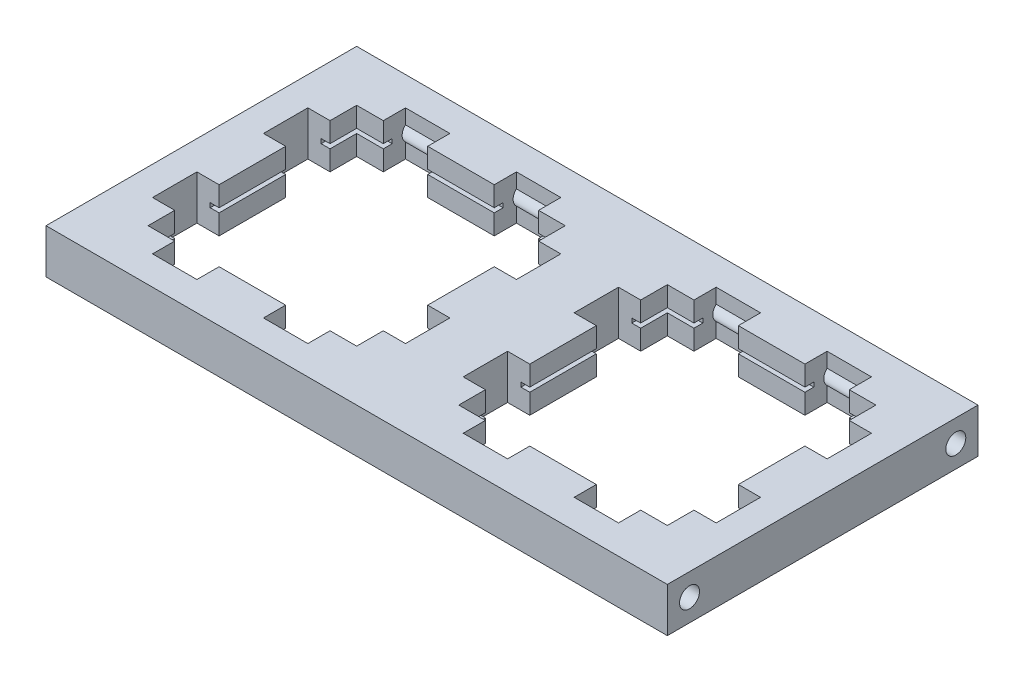
SolidWorks part; units mm, degrees
ref_plane "Front Plane" through (0, 0, 0) normal (0, 0, 1) x (1, 0, 0)
ref_plane "Top Plane" through (0, 0, 0) normal (0, 1, 0) x (1, 0, 0)
ref_plane "Right Plane" through (0, 0, 0) normal (1, 0, 0) x (0, 0, -1)
sketch "Sketch1" plane through (0, 0, 0) normal (0, 1, 0) x (1, 0, 0)
  line L1 (-70, -35) -> (70, -35)
  line L2 (-70, -35) -> (-70, 35)
  line L3 (-70, 35) -> (70, 35)
  line L4 (70, -35) -> (70, 35)
  line L5 (-70, -35) -> (70, 35) construction
  line L6 (-70, 35) -> (70, -35) construction
  point P0 (0, 0)
  dimension "D1" = 70
  dimension "D2" = 140
extrude "Boss-Extrude1" add sketch "Sketch1" along normal mid plane 10
sketch "Sketch2" plane through (70, 0, 0) normal (1, 0, 0) x (0, 0, -1)
  line L0 (-30, 0) -> (30, 0) construction
  line L1 (-35, 5) -> (-30, 0) construction
  circle A0 centre (-30, 0) radius 2.25
  circle A1 centre (30, 0) radius 2.25
  dimension "D1" = 4.5
  dimension "D2" = 45
extrude "Cut-Extrude1" cut sketch "Sketch2" against normal through all
sketch "Sketch3" plane through (0, 0, 0) normal (0, 1, 0) x (1, 0, 0)
  line L0 (-70, 35) -> (-9.5, -25.5) construction
  line L1 (-60.5, 25.5) -> (-9.5, 25.5)
  line L2 (-60.5, 25.5) -> (-60.5, -25.5)
  line L3 (-60.5, -25.5) -> (-9.5, -25.5)
  line L4 (-9.5, 25.5) -> (-9.5, -25.5)
  point P4 (-9.5, 0)
  dimension "D1" = 51
extrude "Cut-Extrude2" cut sketch "Sketch3" against normal mid plane 1
sketch "Sketch4" plane through (0, 5, 0) normal (0, 1, 0) x (1, 0, 0)
  line L8 (-11.5, 23.5) -> (-58.5, 23.5)
  line L9 (-11.5, -23.5) -> (-11.5, 23.5)
  line L10 (-58.5, -23.5) -> (-11.5, -23.5)
  line L11 (-58.5, 23.5) -> (-58.5, -23.5)
  line L12 (-11.5, 23.5) -> (-58.5, 23.5)
  line L13 (-11.5, -23.5) -> (-11.5, 23.5)
  line L14 (-58.5, -23.5) -> (-11.5, -23.5)
  line L15 (-58.5, 23.5) -> (-58.5, -23.5)
  dimension "D1" = 2
extrude "Cut-Extrude3" cut sketch "Sketch4" against normal through all
sketch "Sketch5" plane through (0, 5, 0) normal (0, 1, 0) x (1, 0, 0)
  line L0 (-11.5, 23.5) -> (-58.5, 23.5) construction
  line L1 (-52.5, 23.5) -> (-42.5, 23.5)
  line L2 (-52.5, 23.5) -> (-52.5, 28.5)
  line L3 (-52.5, 28.5) -> (-42.5, 28.5)
  line L4 (-42.5, 23.5) -> (-42.5, 28.5)
  line L5 (-11.5, -23.5) -> (-11.5, 23.5) construction
  line L6 (-27.5, 23.5) -> (-17.5, 23.5)
  line L7 (-27.5, 23.5) -> (-27.5, 28.5)
  line L8 (-27.5, 28.5) -> (-17.5, 28.5)
  line L9 (-17.5, 23.5) -> (-17.5, 28.5)
  line L10 (-11.5, 17.5) -> (-6.5, 17.5)
  line L11 (-11.5, 17.5) -> (-11.5, 7.5)
  line L12 (-11.5, 7.5) -> (-6.5, 7.5)
  line L13 (-6.5, 17.5) -> (-6.5, 7.5)
  line L14 (-58.5, -23.5) -> (-11.5, -23.5) construction
  line L15 (-11.5, -7.5) -> (-6.5, -7.5)
  line L16 (-11.5, -7.5) -> (-11.5, -17.5)
  line L17 (-11.5, -17.5) -> (-6.5, -17.5)
  line L18 (-6.5, -7.5) -> (-6.5, -17.5)
  line L19 (-17.5, -23.5) -> (-27.5, -23.5)
  line L20 (-17.5, -23.5) -> (-17.5, -28.5)
  line L21 (-17.5, -28.5) -> (-27.5, -28.5)
  line L22 (-27.5, -23.5) -> (-27.5, -28.5)
  line L23 (-58.5, 23.5) -> (-58.5, -23.5) construction
  line L24 (-42.5, -23.5) -> (-52.5, -23.5)
  line L25 (-42.5, -23.5) -> (-42.5, -28.5)
  line L26 (-42.5, -28.5) -> (-52.5, -28.5)
  line L27 (-52.5, -23.5) -> (-52.5, -28.5)
  line L28 (-58.5, -17.5) -> (-63.5, -17.5)
  line L29 (-58.5, -17.5) -> (-58.5, -7.5)
  line L30 (-58.5, -7.5) -> (-63.5, -7.5)
  line L31 (-63.5, -17.5) -> (-63.5, -7.5)
  line L32 (-61, 7.5) -> (-61, -7.5) construction
  line L33 (-58.5, 7.5) -> (-63.5, 7.5)
  line L34 (-58.5, 7.5) -> (-58.5, 17.5)
  line L35 (-58.5, 17.5) -> (-63.5, 17.5)
  line L36 (-63.5, 7.5) -> (-63.5, 17.5)
  line L37 (-9, 7.5) -> (-9, -7.5) construction
  line L38 (-27.5, -26) -> (-42.5, -26) construction
  line L39 (-27.5, 26) -> (-42.5, 26) construction
  point P48 (-9, 0)
  point P49 (-11.5, 0)
  point P50 (-35, 26)
  point P51 (-35, 23.5)
  dimension "D1" = 5
  dimension "D2" = 10
  dimension "D3" = 15
extrude "Cut-Extrude4" cut sketch "Sketch5" against normal through all
mirror "Mirror1" about plane through (0, 0, 0) normal (1, 0, 0) of "Cut-Extrude4", "Cut-Extrude3", "Cut-Extrude2"
